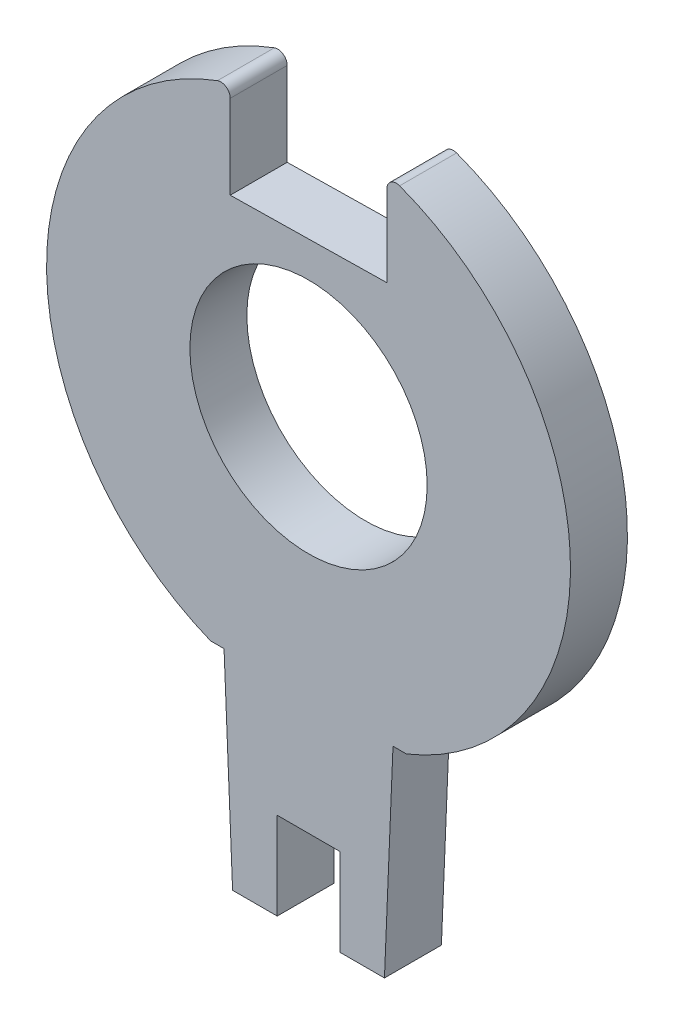
SolidWorks part; units mm, degrees
material "Простая углеродистая сталь"
ref_plane "Спереди" through (0, 0, 0) normal (0, 0, 1) x (1, 0, 0)
ref_plane "Сверху" through (0, 0, 0) normal (0, 1, 0) x (1, 0, 0)
ref_plane "Справа" through (0, 0, 0) normal (1, 0, 0) x (0, 0, -1)
sketch "Эскиз1" plane through (0, 0, 0) normal (0, 0, 1) x (1, 0, 0)
  line L0 (-5.1575, -12.8) -> (-4.45, -12.8)
  line L1 (0, -19) -> (0, -12.8) construction
  line L2 (4, -23.6) -> (1.65, -23.6)
  line L3 (-4.45, -12.8) -> (-4, -23.6)
  line L4 (4, -23.6) -> (4.45, -12.8)
  line L5 (4.45, -12.8) -> (5.1575, -12.8)
  line L6 (-1.65, -23.6) -> (-4, -23.6)
  line L7 (-1.65, -23.6) -> (-1.65, -19)
  line L8 (1.65, -23.6) -> (1.65, -19)
  line L9 (1.65, -19) -> (-1.65, -19)
  line L11 (-4.125, 8.05) -> (-4.125, 12.4699)
  line L12 (4.125, 12.4699) -> (4.125, 8.1852)
  line L13 (-4.125, 8.05) -> (4.125, 8.1852)
  arc A0 (5.1575, -12.8) -> (4.7989, 12.9387) centre (0, 0) ccw
  circle A1 centre (0, 0) radius 6.25
  circle A2 centre (0, 0) radius 12.8 construction
  arc A3 (-4.7989, 12.9387) -> (-5.1575, -12.8) centre (0, 0) ccw
  arc A4 (4.7989, 12.9387) -> (4.125, 12.4699) centre (4.625, 12.4699) ccw
  arc A5 (-4.125, 12.4699) -> (-4.7989, 12.9387) centre (-4.625, 12.4699) ccw
  point P8 (0, -12.8)
  point P9 (-4.45, -12.8)
  point P10 (4.45, -12.8)
  point P27 (-4.125, 13.1691)
  dimension "D1" = 0.5
extrude "Бобышка-Вытянуть1" add sketch "Эскиз1" along normal blind 3
